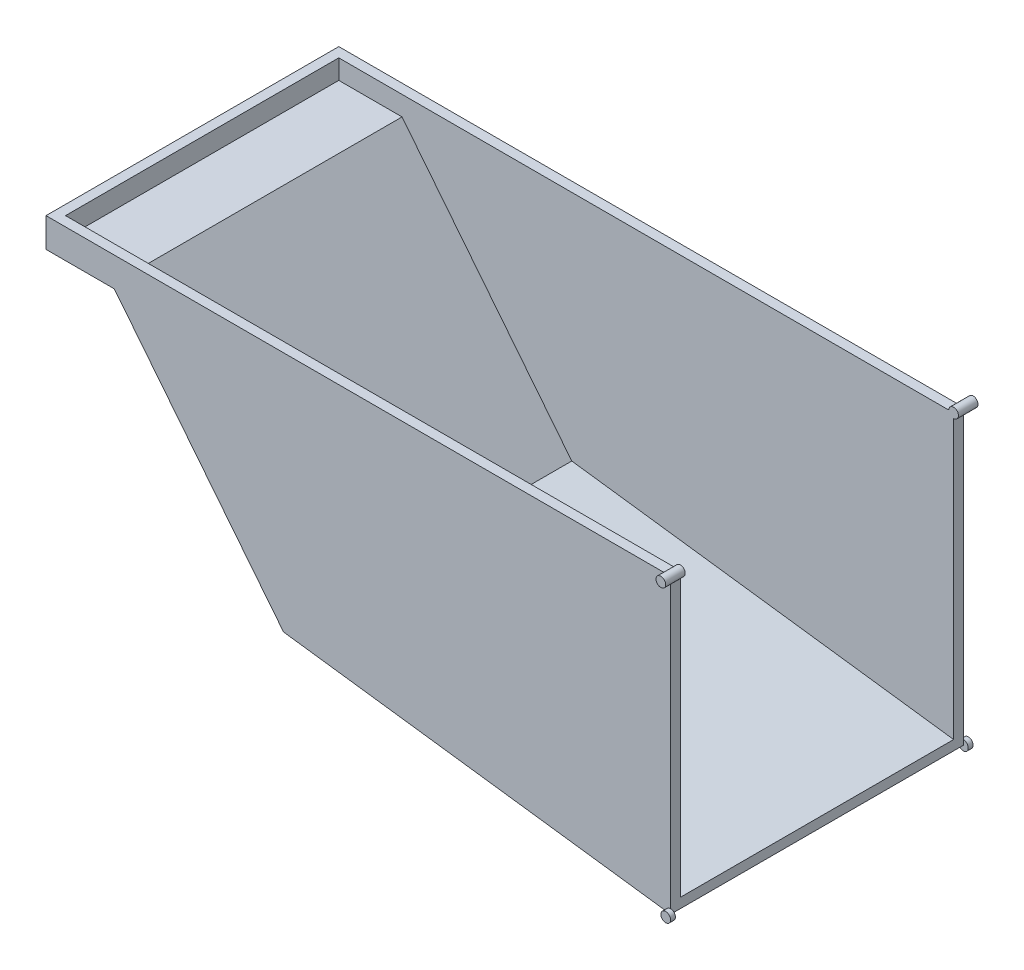
SolidWorks part; units mm, degrees
ref_plane "Front Plane" through (0, 0, 0) normal (0, 0, 1) x (1, 0, 0)
ref_plane "Top Plane" through (0, 0, 0) normal (0, 1, 0) x (1, 0, 0)
ref_plane "Right Plane" through (0, 0, 0) normal (1, 0, 0) x (0, 0, -1)
sketch "Sketch1" plane through (0, 0, 0) normal (0, 0, 1) x (1, 0, 0)
  line L0 (0, 135) -> (35, 135)
  line L1 (0, 0) -> (320, 0)
  line L2 (0, 0) -> (0, 150)
  line L3 (0, 150) -> (320, 150)
  line L4 (320, 0) -> (320, 150)
  line L5 (35, 135) -> (121.711, 26.1052)
  line L6 (121.711, 26.1052) -> (320, 0)
  point P10 (270, 0)
  dimension "D1" = 320
  dimension "D2" = 150
  dimension "D3" = 200
  dimension "D4" = 15
  dimension "D5" = 7.5
  dimension "D6" = 35
  dimension "D7" = 50
extrude "Boss-Extrude2" add sketch "Sketch1" along normal blind 150 contours L5 L6 L4 L3 L2 L0
shell "Shell1" thickness 5
sketch "Sketch2" plane through (0, 0, 150) normal (0, 0, 1) x (1, 0, 0)
  circle A0 centre (320, 150) radius 2.5
  dimension "D1" = 5
extrude "Boss-Extrude4" add sketch "Sketch2" along normal blind 5 and the other way blind 5
sketch "Sketch3" plane through (0, 0, 0) normal (0, 0, -1) x (-1, 0, 0)
  circle A0 centre (-320, 150) radius 2.5
  dimension "D1" = 5
extrude "Boss-Extrude5" add sketch "Sketch3" along normal blind 5 and the other way blind 5
sketch "Sketch4" plane through (0, 0, 150) normal (0, 0, 1) x (1, 0, 0)
  circle A0 centre (320, 0) radius 2.5
  dimension "D1" = 5
extrude "Boss-Extrude7" add sketch "Sketch4" along normal blind 2.5
ref_plane "Plane1" through (0, 0, 75) normal (0, 0, 1) x (1, 0, 0)
mirror "Mirror1" about plane through (0, 0, 75) normal (0, 0, 1) of "Boss-Extrude7"
sketch "Sketch6" plane through (0, 135, 0) normal (0, -1, 0) x (1, 0, 0)
  line L0 (0, 150) -> (35, 0)
  line L2 (16.25, 76) -> (18.75, 76)
  line L3 (16.25, 76) -> (16.25, 74)
  line L4 (0, 0) -> (35, 0)
  line L5 (35, 0) -> (35, 150)
  line L6 (35, 150) -> (0, 150)
  line L7 (0, 150) -> (0, 0)
  line L8 (0, 0) -> (35, 0)
  line L9 (35, 0) -> (35, 150)
  line L10 (35, 150) -> (0, 150)
  line L11 (0, 150) -> (0, 0)
  line L12 (16.25, 74) -> (18.75, 74)
  line L13 (18.75, 76) -> (18.75, 74)
  line L14 (16.25, 76) -> (18.75, 74) construction
  line L15 (16.25, 74) -> (18.75, 76) construction
  point P4 (17.5, 75)
  dimension "D2" = 2
  dimension "D3" = 2.5
  dimension "D1" = 0
extrude "Boss-Extrude8" add sketch "Sketch6" along normal blind 5.5 contours L3 L12 L0 L2 | L13 L2 L0 L12
sketch "Sketch7" plane through (0, 0, 76) normal (0, 0, 1) x (1, 0, 0)
  line L0 (17.5, 135) -> (17.5, 129.5) construction
  line L1 (16.25, 135) -> (16.5019, 130.9381)
  line L2 (18.75, 135) -> (18.4981, 130.9381)
  line L3 (0, 135) -> (35, 135) construction
  line L4 (18.75, 135) -> (16.25, 135)
  line L5 (16.25, 135) -> (16.25, 129.5)
  line L6 (16.25, 129.5) -> (18.75, 129.5)
  line L7 (18.75, 129.5) -> (18.75, 135)
  line L9 (16.25, 135) -> (16.25, 129.5)
  line L10 (16.25, 129.5) -> (18.75, 129.5)
  line L11 (18.75, 129.5) -> (18.75, 135)
  circle A0 centre (17.5, 131) radius 0.75
  arc A1 (16.5019, 130.9381) -> (18.4981, 130.9381) centre (17.5, 131) ccw
  dimension "D2" = 1.5
  dimension "D3" = 2
  dimension "D4" = 4
  dimension "D1" = 0
extrude "Cut-Extrude1" cut sketch "Sketch7" against normal blind 5.5
